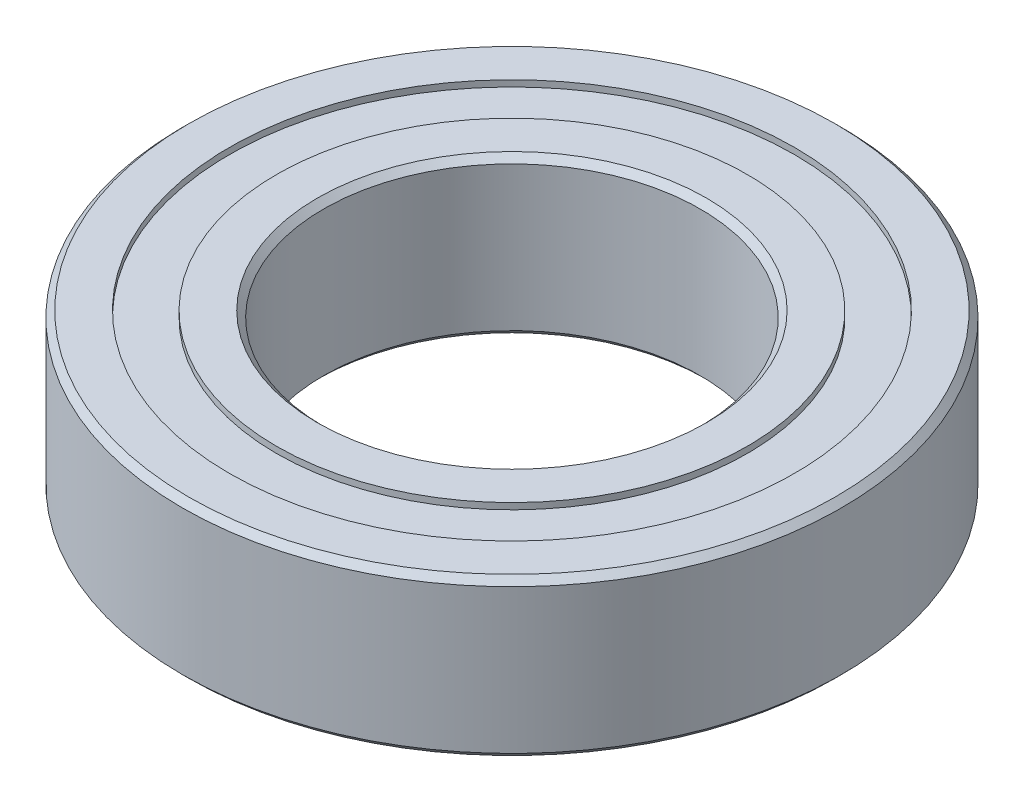
SolidWorks part; units mm, degrees
ref_plane "Front Plane" through (0, 0, 0) normal (0, 0, 1) x (1, 0, 0)
ref_plane "Top Plane" through (0, 0, 0) normal (0, 1, 0) x (1, 0, 0)
ref_plane "Right Plane" through (0, 0, 0) normal (1, 0, 0) x (0, 0, -1)
sketch "Sketch1" plane through (0, 0, 0) normal (0, 1, 0) x (1, 0, 0)
  circle A0 centre (0, 0) radius 10.5
  circle A1 centre (0, 0) radius 6
  dimension "D1" = 21
  dimension "D2" = 12
extrude "Boss-Extrude1" add sketch "Sketch1" along normal blind 5
sketch "Sketch2" plane through (0, 5, 0) normal (0, 1, 0) x (1, 0, 0)
  circle A4 centre (0, 0) radius 9
  circle A5 centre (0, 0) radius 9
  circle A7 centre (0, 0) radius 7.5
  circle A8 centre (0, 0) radius 7.5
  dimension "D1" = 1.5
  dimension "D2" = 1.5
extrude "Cut-Extrude1" cut sketch "Sketch2" against normal blind 0.2
sketch "Sketch3" plane through (0, 0, 0) normal (0, -1, 0) x (1, 0, 0)
  circle A1 centre (0, 0) radius 7.5 construction
  circle A4 centre (0, 0) radius 9 construction
  circle A7 centre (0, 0) radius 7.5
  circle A8 centre (0, 0) radius 9
extrude "Cut-Extrude2" cut sketch "Sketch3" against normal blind 0.2
chamfer "Chamfer1" distance 0.2 angle 45 4 edges at (0, 5, 10.5) (0, 0, 10.5) (0, 5, 6) (0, 0, 6)
